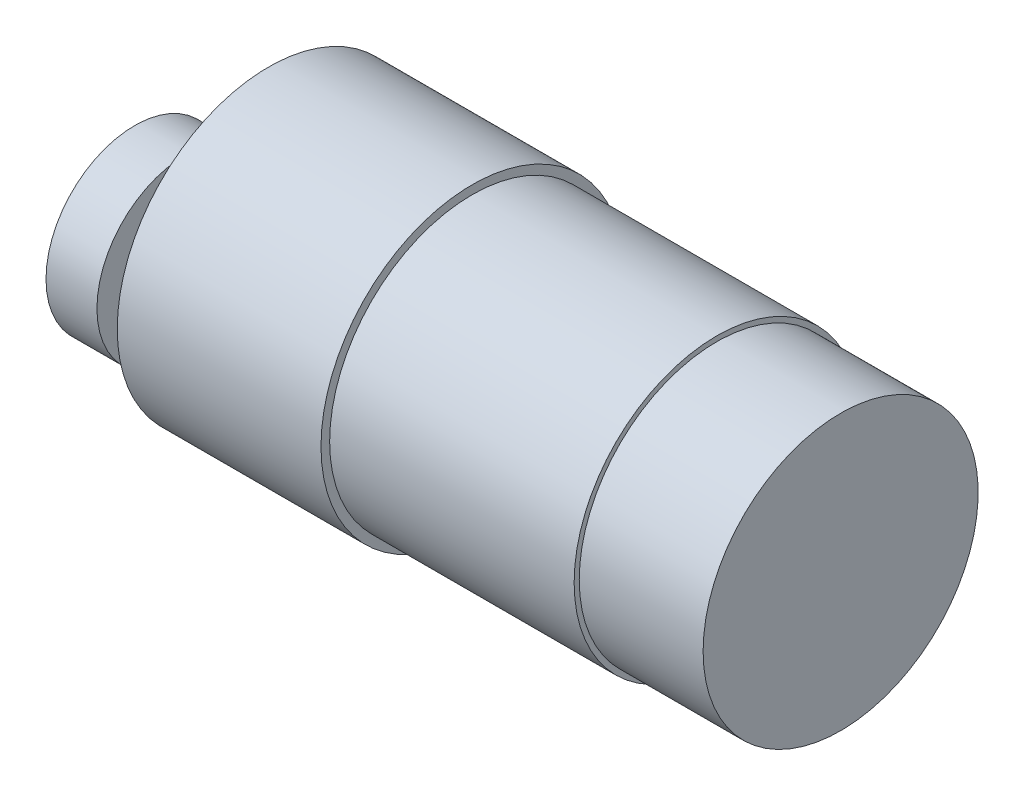
SolidWorks part; units mm, degrees
ref_plane "Face" through (0, 0, 0) normal (0, 0, 1) x (1, 0, 0)
ref_plane "Dessus" through (0, 0, 0) normal (0, 1, 0) x (1, 0, 0)
ref_plane "Droite" through (0, 0, 0) normal (1, 0, 0) x (0, 0, -1)
sketch "Esquisse6" plane through (0, 0, 0) normal (1, 0, 0) x (0, 0, -1)
  circle A0 centre (0, 0) radius 18.8595
  dimension "D1" = 37.719
extrude "Boss.-Extru.2" add sketch "Esquisse6" along normal blind 25.4
sketch "Esquisse7" plane through (25.4, 0, 0) normal (1, 0, 0) x (0, 0, -1)
  circle A0 centre (0, 0) radius 17.78
  dimension "D1" = 35.56
extrude "Boss.-Extru.3" add sketch "Esquisse7" along normal blind 30.48
sketch "Esquisse8" plane through (55.88, 0, 0) normal (1, 0, 0) x (0, 0, -1)
  circle A0 centre (0, 0) radius 17.145
  dimension "D1" = 34.29
extrude "Boss.-Extru.4" add sketch "Esquisse8" along normal blind 15.4432
sketch "Esquisse9" plane through (0, 0, 0) normal (-1, 0, 0) x (0, 0, 1)
  circle A0 centre (0, -6.858) radius 5.969
  dimension "D1" = 11.938
  dimension "D2" = 6.858
extrude "Boss.-Extru.5" add sketch "Esquisse9" along normal blind 6.096
sketch "Esquisse10" plane through (-6.096, 0, 0) normal (-1, 0, 0) x (0, 0, 1)
  circle A0 centre (0, -6.858) radius 4.699
  circle A1 centre (0, -6.858) radius 5.969 construction
  dimension "D1" = 9.398
extrude "Boss.-Extru.6" add sketch "Esquisse10" along normal blind 4.2333
sketch "Esquisse11" plane through (-10.3293, 0, 0) normal (-1, 0, 0) x (0, 0, 1)
  circle A0 centre (0, -6.858) radius 11.0617
  circle A1 centre (0, -6.858) radius 4.699 construction
  dimension "D1" = 22.1234
extrude "Boss.-Extru.7" add sketch "Esquisse11" along normal blind 6.35
sketch "Esquisse12" plane through (-16.6793, 0, 0) normal (-1, 0, 0) x (0, 0, 1)
  circle A0 centre (0, -6.858) radius 4.7752
  circle A1 centre (0, -6.858) radius 11.0617 construction
  dimension "D1" = 9.5504
extrude "Boss.-Extru.8" add sketch "Esquisse12" along normal blind 3.302
hole_wizard "Perçage pour tuyau pour trou taraudé 1/161" positions "Esquisse13" profile "Esquisse15" hole size "1/16" standard "Ansi Inch"
sketch "Esquisse13" plane through (-19.9813, 0, 0) normal (-1, 0, 0) x (0, 0, 1)
  circle A1 centre (0, -6.858) radius 4.7752 construction
  point P0 (0, -6.858)
sketch "Esquisse15" plane through (-19.9813, -6.858, 0) normal (0, 1, 0) x (0, 0, 1)
  line L0 (0, 0) -> (0, 19.9813)
  line L1 (0, 19.9813) -> (3.0734, 19.9813)
  line L2 (3.0734, 19.9813) -> (3.0734, 0)
  line L5 (3.0734, 0) -> (0, 0)
  line L10 (0, 19.9813) -> (-3.0734, 19.9813) construction
  line L11 (0, -6.35) -> (0, 107.95) construction
  dimension "Diamètre du perçage" = 6.1468
  dimension "Profondeur du perçage" = 19.9813
  dimension "Angle de pointe" = 180
sketch "Esquisse16" plane through (0, 0, 0) normal (-1, 0, 0) x (0, 0, 1)
  line L0 (-1.778, -4.4768) -> (1.778, -4.4768)
  arc A0 (-1.778, -4.4768) -> (1.778, -4.4768) centre (0, -6.858) ccw
  point P5 (0, -4.4768)
  dimension "D1" = 5.9436
  dimension "D2" = 3.556
extrude "Boss.-Extru.9" add sketch "Esquisse16" along normal up to surface (19.9813 mm away) up to face at (-19.9813, -6.858, 3.0734)
sketch "Esquisse17" plane through (-19.9813, 0, 0) normal (-1, 0, 0) x (0, 0, 1)
  line L0 (-1.778, -4.4768) -> (1.778, -4.4768)
  arc A3 (-1.778, -4.4768) -> (1.778, -4.4768) centre (0, -6.858) ccw
extrude "Boss.-Extru.10" add sketch "Esquisse17" along normal blind 2.032
sketch "Esquisse18" plane through (-16.6793, 0, 0) normal (-1, 0, 0) x (0, 0, 1)
  circle A1 centre (0, -0.254) radius 1.4605
  circle A2 centre (0, -6.858) radius 4.7752 construction
  circle A3 centre (6.604, -6.858) radius 1.4605
  circle A4 centre (0, -13.462) radius 1.4605
  circle A5 centre (-6.604, -6.858) radius 1.4605
  point P15 (0, -6.858)
  dimension "D2" = 2.921
  dimension "D1" = 6.604
  dimension "D3" = 4
extrude "Enlèv. mat.-Extru.2" cut sketch "Esquisse18" against normal up to next
sketch "Esquisse19" plane through (0, 0, 0) normal (-1, 0, 0) x (0, 0, 1)
  circle A1 centre (6.3762, 14.7894) radius 1.5
  circle A2 centre (7.2533, -15.5106) radius 1.5
  circle A3 centre (-16.8094, 1.555) radius 1.5
  point P12 (0.1484, -0.0315)
  dimension "D1" = 3
  dimension "D3" = 26.6969
  dimension "D2" = 3
  dimension "D4" = 3
  dimension "D5" = 29.5
extrude "Enlèv. mat.-Extru.3" cut sketch "Esquisse19" against normal blind 5
